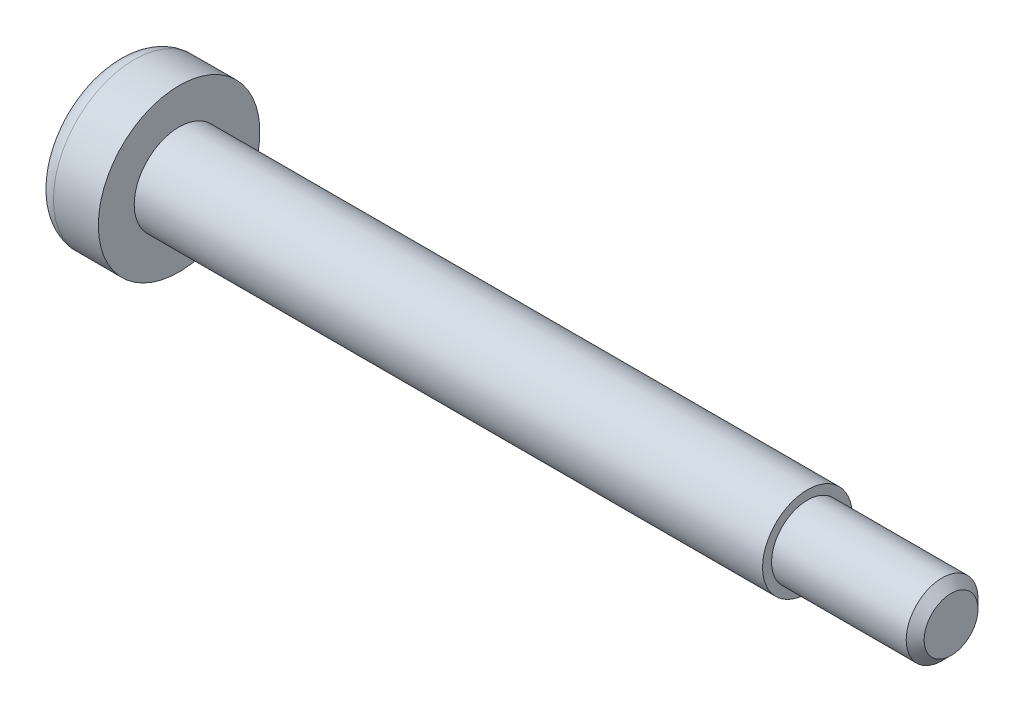
SolidWorks part; units mm, degrees
material "不锈钢 (铁素体)"
ref_plane "前视基准面" through (0, 0, 0) normal (0, 0, 1) x (1, 0, 0)
ref_plane "上视基准面" through (0, 0, 0) normal (0, 1, 0) x (1, 0, 0)
ref_plane "右视基准面" through (0, 0, 0) normal (1, 0, 0) x (0, 0, -1)
sketch "草图1" plane through (0, 0, 0) normal (0, 0, 1) x (1, 0, 0)
  line L0 (0, 0) -> (46.5, 0) construction
  line L1 (0, 0) -> (0, 4.5)
  line L2 (0, 4.5) -> (3.5, 4.5)
  line L3 (3.5, 4.5) -> (3.5, 2.5)
  line L4 (3.5, 2.5) -> (38.5, 2.5)
  line L5 (38.5, 2.5) -> (38.5, 2)
  line L6 (38.5, 2) -> (46.5, 2)
  line L7 (46.5, 2) -> (46.5, 0)
  line L8 (0, 0) -> (46.5, 0)
  dimension "D1" = 9
  dimension "D2" = 5
  dimension "D3" = 4
  dimension "D4" = 8
  dimension "D5" = 3.5
  dimension "D6" = 35
revolve "旋转1" add sketch "草图1" angle 360 about L0
cosmetic thread "装饰螺纹线1"
sketch "草图2" plane through (0, 0, 0) normal (-1, 0, 0) x (0, 0, 1)
  line L0 (0, 0) -> (0, 1.7321) construction
  line L1 (0, 1.7321) -> (-1.5, 0.866)
  line L2 (-1.5, 0.866) -> (-1.5, -0.866)
  line L3 (-1.5, -0.866) -> (0, -1.7321)
  line L4 (0, -1.7321) -> (1.5, -0.866)
  line L5 (1.5, -0.866) -> (1.5, 0.866)
  line L6 (1.5, 0.866) -> (0, 1.7321)
  circle A0 centre (0, 0) radius 1.5 construction
  dimension "D1" = 3
extrude "切除-拉伸1" cut sketch "草图2" against normal blind 2.4
fillet "圆角1" radius 1 1 edges at (0, 0, 4.5)
chamfer "倒角1" distance 0.5 angle 45 1 edges at (46.5, 0, 2)
